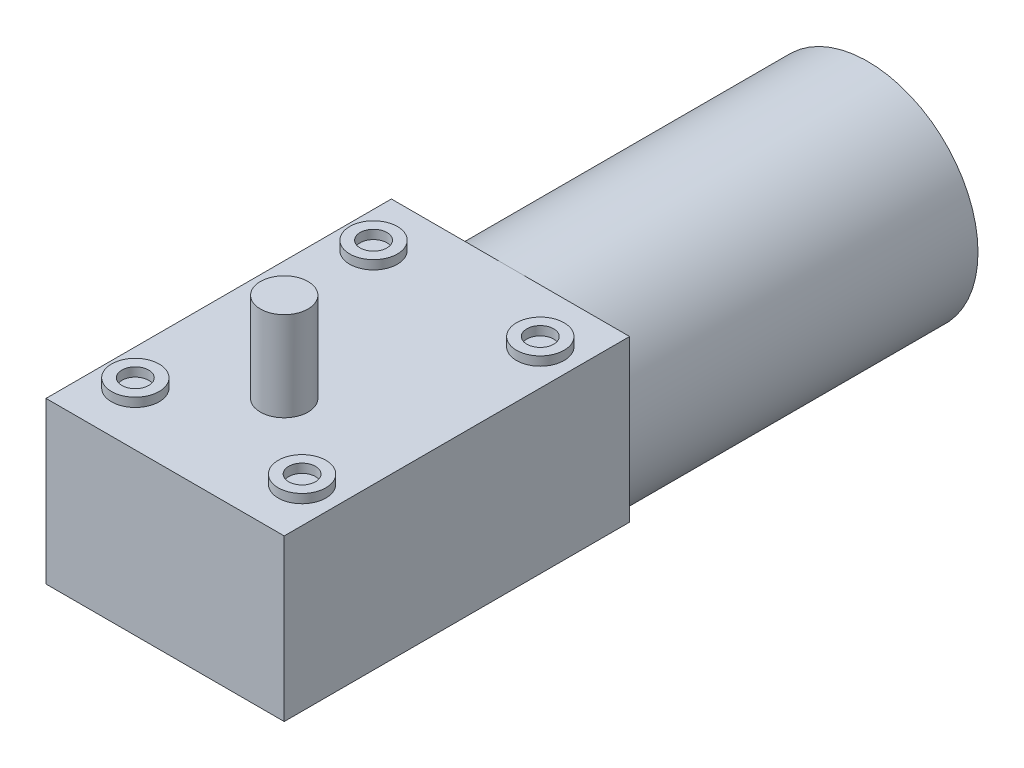
SolidWorks part; units mm, degrees
ref_plane "Front" through (0, 0, 0) normal (0, 0, 1) x (1, 0, 0)
ref_plane "Top" through (0, 0, 0) normal (0, 1, 0) x (1, 0, 0)
ref_plane "Right" through (0, 0, 0) normal (1, 0, 0) x (0, 0, -1)
sketch "Sketch1" plane through (0, 0, 0) normal (0, 0, 1) x (1, 0, 0)
  circle A0 centre (0, 0) radius 18.5
  dimension "D1" = 37
extrude "Boss-Extrude1" add sketch "Sketch1" along normal blind 60
sketch "Sketch2" plane through (0, 0, 60) normal (0, 0, 1) x (1, 0, 0)
  line L1 (-20, 18.5) -> (20, 18.5)
  line L2 (-20, 18.5) -> (-20, -18.5)
  line L3 (-20, -18.5) -> (20, -18.5)
  line L4 (20, 18.5) -> (20, -18.5)
  line L5 (-20, 18.5) -> (20, -18.5) construction
  line L6 (-20, -18.5) -> (20, 18.5) construction
  point P0 (0, 0)
  dimension "D1" = 40
  dimension "D2" = 37
extrude "Boss-Extrude2" add sketch "Sketch2" along normal blind 58
sketch "Sketch3" plane through (0, 18.5, 0) normal (0, 1, 0) x (1, 0, 0)
  line L0 (0, -118) -> (0, -98) construction
  line L1 (20, -118) -> (-20, -118) construction
  circle A0 centre (0, -98) radius 4
  dimension "D1" = 8
  dimension "D2" = 20
extrude "Boss-Extrude3" add sketch "Sketch3" along normal blind 15
sketch "Sketch4" plane through (0, 0, 118) normal (0, 0, 1) x (1, 0, 0)
  line L0 (-20, 18.5) -> (-20, -18.5) construction
  line L1 (20, -18.5) -> (-20, -18.5)
  line L2 (20, -18.5) -> (20, -8.5)
  line L3 (20, -8.5) -> (-20, -8.5)
  line L4 (-20, -18.5) -> (-20, -8.5)
  line L5 (20, 18.5) -> (-20, 18.5) construction
  dimension "D1" = 27
extrude "Cut-Extrude1" cut sketch "Sketch4" against normal up to surface (58 mm away) and the other way through all up to face at (-14.625, 0, 60)
sketch "Sketch5" plane through (0, 18.5, 0) normal (0, 1, 0) x (1, 0, 0)
  line L2 (20, -60) -> (-20, -118) construction
  line L3 (0, -109) -> (0, -104.4234) construction
  line L4 (14, -69) -> (-14, -69) construction
  line L5 (14, -69) -> (14, -109) construction
  line L6 (14, -109) -> (-14, -109) construction
  line L7 (-14, -69) -> (-14, -109) construction
  line L8 (14, -69) -> (-14, -109) construction
  line L9 (14, -109) -> (-14, -69) construction
  circle A0 centre (14, -69) radius 4
  circle A1 centre (14, -69) radius 2.25
  circle A2 centre (14, -109) radius 2.25
  circle A3 centre (14, -109) radius 4
  circle A4 centre (-14, -109) radius 4
  circle A5 centre (-14, -109) radius 2.25
  circle A6 centre (-14, -69) radius 2.25
  circle A7 centre (-14, -69) radius 4
  point P0 (0, -89)
  dimension "D3" = 4.5
  dimension "D4" = 8
  dimension "D1" = 40
  dimension "D2" = 28
extrude "Boss-Extrude4" add sketch "Sketch5" along normal blind 1.5
sketch "Sketch6" plane through (0, 18.5, 0) normal (0, 1, 0) x (1, 0, 0)
  line L0 (-20, -60) -> (20, -60)
  dimension "D1" = 40
sketch "Sketch7" plane through (0, 18.5, 0) normal (0, 1, 0) x (1, 0, 0)
  line L0 (-14, -109) -> (14, -109) construction
  line L5 (14, -109) -> (14, -69) construction
  line L6 (14, -69) -> (-14, -69) construction
  line L7 (-14, -69) -> (-14, -109) construction
  line L8 (-14, -89) -> (14, -89) construction
  line L9 (-4, -98) -> (4, -98) construction
  line L10 (0, -94) -> (0, -102) construction
  circle A1 centre (0, -98) radius 4 construction
  circle A2 centre (0, -98) radius 4 construction
  point P22 (0, 0)
  dimension "D1" = 9
  dimension "D2" = 11
  dimension "D3" = 14
